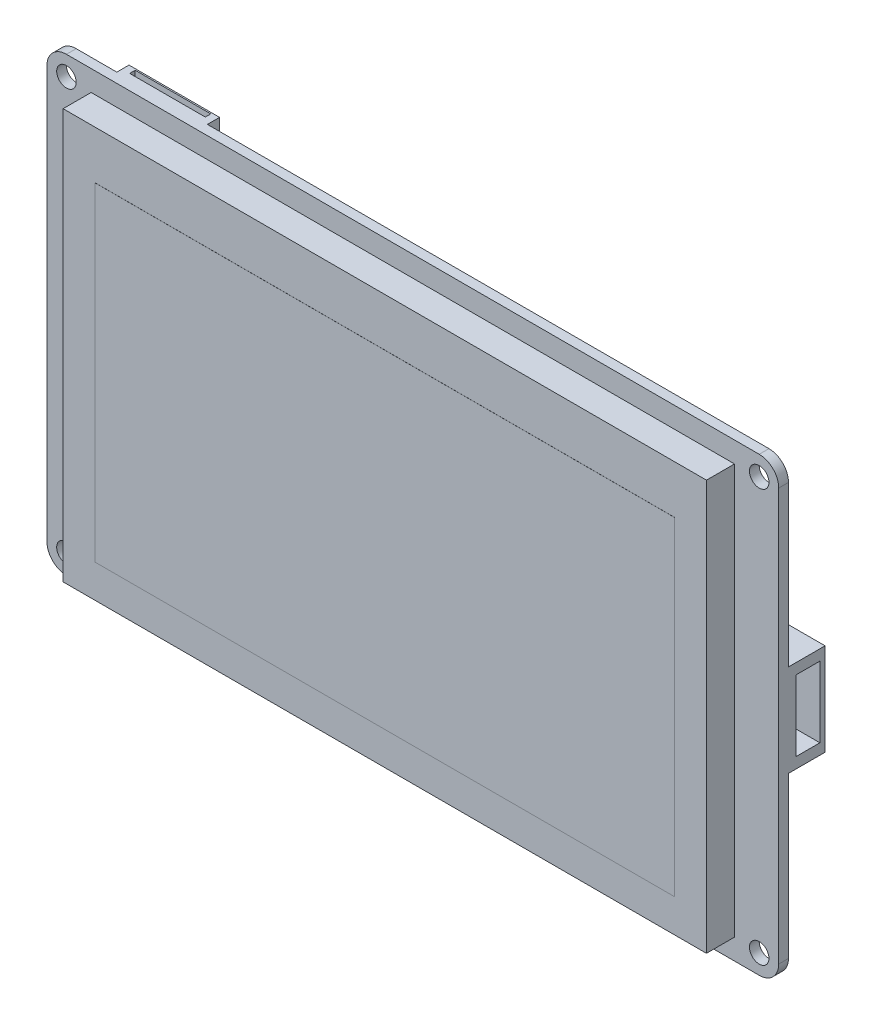
SolidWorks part; units mm, degrees
ref_plane "前视基准面" through (0, 0, 0) normal (0, 0, 1) x (1, 0, 0)
ref_plane "上视基准面" through (0, 0, 0) normal (0, 1, 0) x (1, 0, 0)
ref_plane "右视基准面" through (0, 0, 0) normal (1, 0, 0) x (0, 0, -1)
other "Configuration Table"
sketch "120 x 74 PCB outline profile" plane through (0, 0, 0) normal (0, 0, 1) x (1, 0, 0)
  line L0 (-56.8, -37) -> (56.8, -37)
  line L1 (60, -33.8) -> (60, 33.8)
  line L2 (56.8, 37) -> (-56.8, 37)
  line L3 (-60, 33.8) -> (-60, -33.8)
  arc A0 (56.8, -37) -> (60, -33.8) centre (56.8, -33.8) ccw
  arc A1 (60, 33.8) -> (56.8, 37) centre (56.8, 33.8) ccw
  arc A2 (-56.8, 37) -> (-60, 33.8) centre (-56.8, 33.8) ccw
  arc A3 (-60, -33.8) -> (-56.8, -37) centre (-56.8, -33.8) ccw
extrude "120 x 74 PCB outline" add sketch "120 x 74 PCB outline profile" along normal blind 1.6
sketch "4 x D3.2 - pitch 113.6 x 67.6 profile" plane through (0, 0, 0) normal (0, 0, 1) x (1, 0, 0)
  circle A0 centre (-56.8, -33.8) radius 1.6
  circle A1 centre (-56.8, 33.8) radius 1.6
  circle A2 centre (56.8, -33.8) radius 1.6
  circle A3 centre (56.8, 33.8) radius 1.6
extrude "4 x D3.2 - pitch 113.6 x 67.6" cut sketch "4 x D3.2 - pitch 113.6 x 67.6 profile" along normal blind 1.8 from offset 0.1
sketch "105.50 x 67.20 LCD module profile" plane through (0, 0, 0) normal (0, 0, 1) x (1, 0, 0)
  line L0 (-52.75, -33.6) -> (52.75, -33.6)
  line L1 (52.75, -33.6) -> (52.75, 33.6)
  line L2 (52.75, 33.6) -> (-52.75, 33.6)
  line L3 (-52.75, 33.6) -> (-52.75, -33.6)
extrude "105.50 x 67.20 LCD module" add sketch "105.50 x 67.20 LCD module profile" along normal blind 3.45 from offset 1.55
sketch "Touch panel - black border profile" plane through (0, 0, 0) normal (0, 0, 1) x (1, 0, 0)
  line L0 (-52.75, -33.6) -> (52.75, -33.6)
  line L1 (52.75, -33.6) -> (52.75, 33.6)
  line L2 (52.75, 33.6) -> (-52.75, 33.6)
  line L3 (-52.75, 33.6) -> (-52.75, -33.6)
extrude "Touch panel - black border" add sketch "Touch panel - black border profile" along normal blind 1.22 from offset 4.98
sketch "Visible 480 x 272 display area profile" plane through (0, 0, 0) normal (0, 0, 1) x (1, 0, 0)
  line L0 (-47.52, -28.16) -> (47.52, -28.16)
  line L1 (47.52, -28.16) -> (47.52, 25.7)
  line L2 (47.52, 25.7) -> (-47.52, 25.7)
  line L3 (-47.52, 25.7) -> (-47.52, -28.16)
extrude "Visible 480 x 272 display area" add sketch "Visible 480 x 272 display area profile" along normal blind 0.045 from offset 6.17
sketch "Rear 4-pin UART connector housing profile" plane through (0, 0, 0) normal (0, 0, 1) x (1, 0, 0)
  line L0 (52.19, -7.52) -> (60, -7.52)
  line L1 (60, -7.52) -> (60, 7.6)
  line L2 (60, 7.6) -> (52.19, 7.6)
  line L3 (52.19, 7.6) -> (52.19, -7.52)
extrude "Rear 4-pin UART connector housing" add sketch "Rear 4-pin UART connector housing profile" along normal blind 6.05 from offset 6
sketch "UART connector socket profile" plane through (0, 0, 0) normal (0, 0, 1) x (1, 0, 0)
  line L0 (54.3, -5.75) -> (60.2, -5.75)
  line L1 (60.2, -5.75) -> (60.2, 5.85)
  line L2 (60.2, 5.85) -> (54.3, 5.85)
  line L3 (54.3, 5.85) -> (54.3, -5.75)
extrude "UART connector socket" cut sketch "UART connector socket profile" along normal blind 3.9 from offset 5.15
sketch "Rear card holder profile" plane through (0, 0, 0) normal (0, 0, 1) x (1, 0, 0)
  line L0 (-50.14, 22) -> (-35.29, 22)
  line L1 (-35.29, 22) -> (-35.29, 37)
  line L2 (-35.29, 37) -> (-50.14, 37)
  line L3 (-50.14, 37) -> (-50.14, 22)
extrude "Rear card holder" add sketch "Rear card holder profile" along normal blind 2.05 from offset 2
sketch "Card opening profile" plane through (0, 0, 0) normal (0, 0, 1) x (1, 0, 0)
  line L0 (-48.9, 28.5) -> (-36.5, 28.5)
  line L1 (-36.5, 28.5) -> (-36.5, 37.2)
  line L2 (-36.5, 37.2) -> (-48.9, 37.2)
  line L3 (-48.9, 37.2) -> (-48.9, 28.5)
extrude "Card opening" cut sketch "Card opening profile" along normal blind 0.9 from offset 1.77
